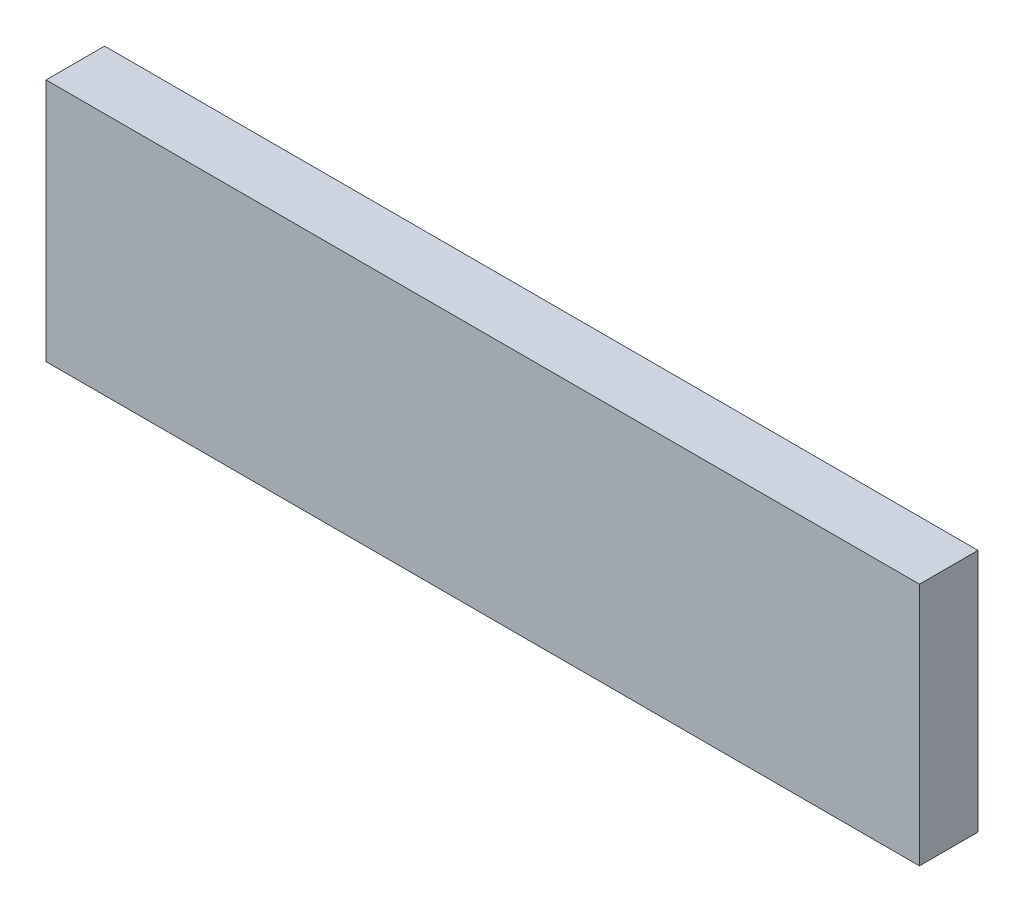
SolidWorks part; units mm, degrees
ref_plane "Plano frontal" through (0, 0, 0) normal (0, 0, 1) x (1, 0, 0)
ref_plane "Plano superior" through (0, 0, 0) normal (0, 1, 0) x (1, 0, 0)
ref_plane "Plano direito" through (0, 0, 0) normal (1, 0, 0) x (0, 0, -1)
sketch "Esboço1" plane through (0, 0, 0) normal (0, 0, 1) x (1, 0, 0)
  line L1 (-89.5, 25) -> (89.5, 25)
  line L2 (-89.5, 25) -> (-89.5, -25)
  line L3 (-89.5, -25) -> (89.5, -25)
  line L4 (89.5, 25) -> (89.5, -25)
  line L5 (-89.5, 25) -> (89.5, -25) construction
  line L6 (-89.5, -25) -> (89.5, 25) construction
  point P0 (0, 0)
extrude "Ressalto-extrusão1" add sketch "Esboço1" along normal mid plane 12
ref_plane "Plano1" through (0, -25, 0) normal (0, -1, 0) x (-1, 0, 0)
sketch "Esboço2" plane through (0, -25, 0) normal (0, -1, 0) x (-1, 0, 0)
  circle A0 centre (81, 0) radius 3
  circle A1 centre (-69, 0) radius 3
extrude "Corte-extrusão1" cut sketch "Esboço2" against normal blind 20
